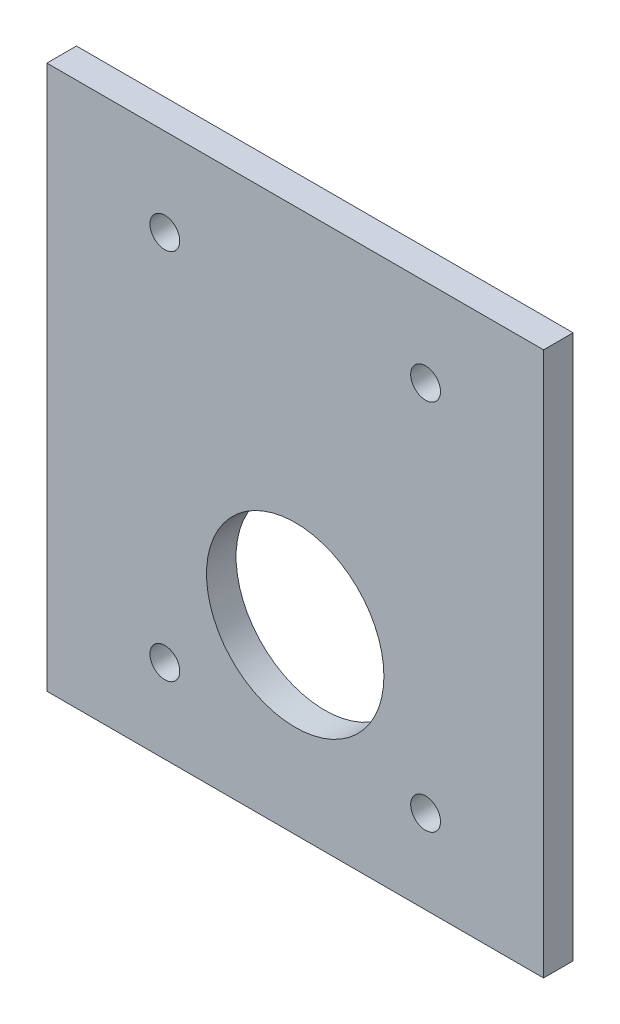
SolidWorks part; units mm, degrees
ref_plane "Front Plane" through (0, 0, 0) normal (0, 0, 1) x (1, 0, 0)
ref_plane "Top Plane" through (0, 0, 0) normal (0, 1, 0) x (1, 0, 0)
ref_plane "Right Plane" through (0, 0, 0) normal (1, 0, 0) x (0, 0, -1)
sketch "Sketch1" plane through (0, 0, 0) normal (0, 0, 1) x (1, 0, 0)
  line L0 (0, -19.5) -> (0, 0) construction
  line L1 (26.67, 38.92) -> (-26.67, 38.92)
  line L2 (26.67, 38.92) -> (26.67, -19.5)
  line L3 (26.67, -19.5) -> (-26.67, -19.5)
  line L4 (-26.67, 38.92) -> (-26.67, -19.5)
  line L5 (26.67, 38.92) -> (-26.67, -19.5) construction
  line L6 (26.67, -19.5) -> (-26.67, 38.92) construction
  line L7 (0, 0) -> (0, 38.92) construction
  line L8 (0, -10.5) -> (0, -19.5) construction
  line L9 (-14, -10.5) -> (14, -10.5) construction
  line L10 (-14, -10.5) -> (-14, 29.5) construction
  line L11 (-14, 29.5) -> (14, 29.5) construction
  line L12 (14, -10.5) -> (14, 29.5) construction
  circle A0 centre (0, 0) radius 9.525
  circle A1 centre (-14, 29.5) radius 1.6
  circle A2 centre (14, 29.5) radius 1.6
  circle A3 centre (14, -10.5) radius 1.6
  circle A4 centre (-14, -10.5) radius 1.6
  point P0 (0, 0)
  dimension "D3" = 19.05
  dimension "D4" = 3.2
  dimension "D1" = 53.34
  dimension "D2" = 58.42
  dimension "D5" = 28
  dimension "D6" = 40
  dimension "D7" = 9
  dimension "D8" = 19.5
extrude "Boss-Extrude1" add sketch "Sketch1" along normal blind 3.175
sketch "Sketch2" plane through (0, 0, 3.175) normal (0, 0, 1) x (1, 0, 0)
  line L0 (-26.67, 38.92) -> (-26.67, -19.5)
  line L1 (-26.67, 38.92) -> (-20.32, 38.92)
  line L2 (-26.67, -19.5) -> (-20.32, -19.5)
  line L3 (-20.32, 38.92) -> (-20.32, -19.5)
  line L4 (26.67, -19.5) -> (26.67, 38.92)
  line L5 (26.67, -19.5) -> (20.32, -19.5)
  line L6 (26.67, 38.92) -> (20.32, 38.92)
  line L7 (20.32, -19.5) -> (20.32, 38.92)
  dimension "D1" = 6.35
  dimension "D2" = 6.35
